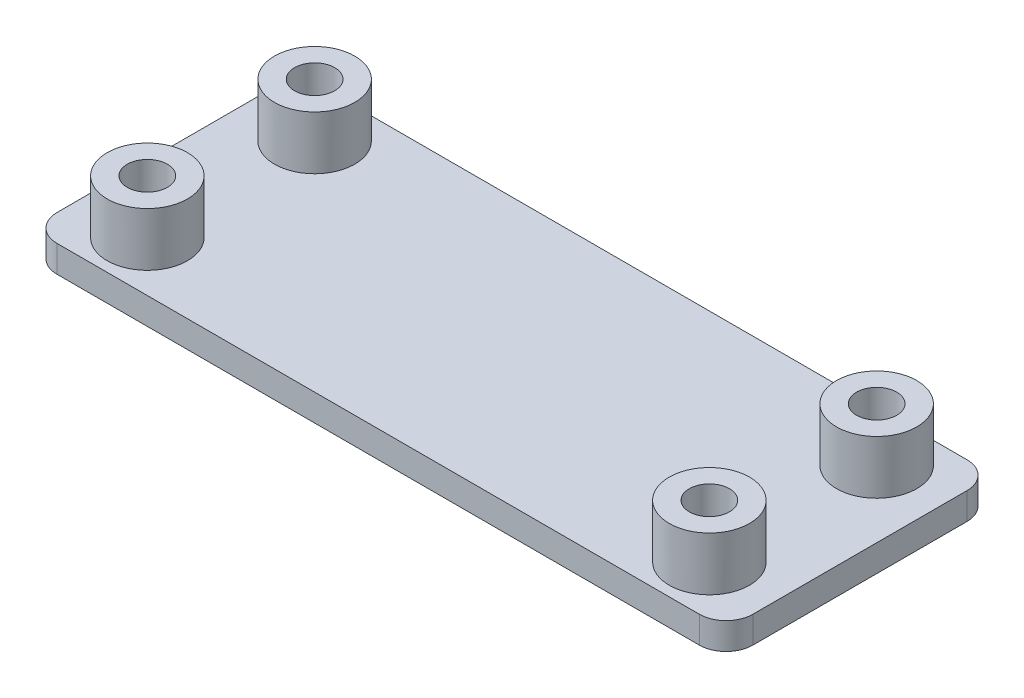
SolidWorks part; units mm, degrees
ref_plane "Płaszczyzna przednia" through (0, 0, 0) normal (0, 0, 1) x (1, 0, 0)
ref_plane "Płaszczyzna górna" through (0, 0, 0) normal (0, 1, 0) x (1, 0, 0)
ref_plane "Płaszczyzna prawa" through (0, 0, 0) normal (1, 0, 0) x (0, 0, -1)
sketch "Sketch1" plane through (0, 0, 0) normal (0, 1, 0) x (1, 0, 0)
  line L1 (0, 0) -> (52, 0)
  line L2 (0, 0) -> (0, 20)
  line L3 (0, 20) -> (52, 20)
  line L4 (52, 0) -> (52, 20)
  dimension "D1" = 20
  dimension "D2" = 52
extrude "Boss-Extrude1" add sketch "Sketch1" along normal blind 2
sketch "Sketch2" plane through (0, 2, 0) normal (0, 1, 0) x (1, 0, 0)
  line L0 (5, 20) -> (5, 16.25) construction
  line L1 (5, 16.25) -> (47, 16.25) construction
  line L2 (5, 16.25) -> (5, 3.75) construction
  line L3 (5, 3.75) -> (47, 3.75) construction
  line L4 (47, 16.25) -> (47, 3.75) construction
  line L5 (52, 20) -> (0, 20) construction
  line L6 (5, 3.75) -> (5, 0) construction
  line L7 (0, 0) -> (52, 0) construction
  line L8 (52, 11.9876) -> (47, 11.9876) construction
  line L9 (52, 0) -> (52, 20) construction
  line L10 (5, 7.5354) -> (0, 7.5354) construction
  line L11 (0, 20) -> (0, 0) construction
  circle A0 centre (5, 16.25) radius 1.5
  circle A1 centre (5, 3.75) radius 1.5
  circle A2 centre (47, 3.75) radius 1.5
  circle A3 centre (47, 16.25) radius 1.5
  circle A4 centre (5, 16.25) radius 3
  circle A5 centre (5, 3.75) radius 3
  circle A6 centre (47, 3.75) radius 3
  circle A7 centre (47, 16.25) radius 3
  dimension "D1" = 3
  dimension "D2" = 1.5
  dimension "D3" = 12.5
  dimension "D4" = 42
extrude "Boss-Extrude2" add sketch "Sketch2" along normal blind 4
sketch "Sketch3" plane through (0, 2, 0) normal (0, 1, 0) x (1, 0, 0)
  circle A0 centre (47, 3.75) radius 1.5 construction
  circle A1 centre (47, 16.25) radius 1.5 construction
  circle A2 centre (5, 3.75) radius 1.5 construction
  circle A3 centre (5, 16.25) radius 1.5 construction
  circle A4 centre (47, 3.75) radius 1.5
  circle A5 centre (47, 16.25) radius 1.5
  circle A6 centre (5, 3.75) radius 1.5
  circle A7 centre (5, 16.25) radius 1.5
extrude "Cut-Extrude1" cut sketch "Sketch3" against normal through all
fillet "Fillet1" radius 2 4 edges at (52, 1, 0) (52, 1, -20) (0, 1, -20) (0, 1, 0)
